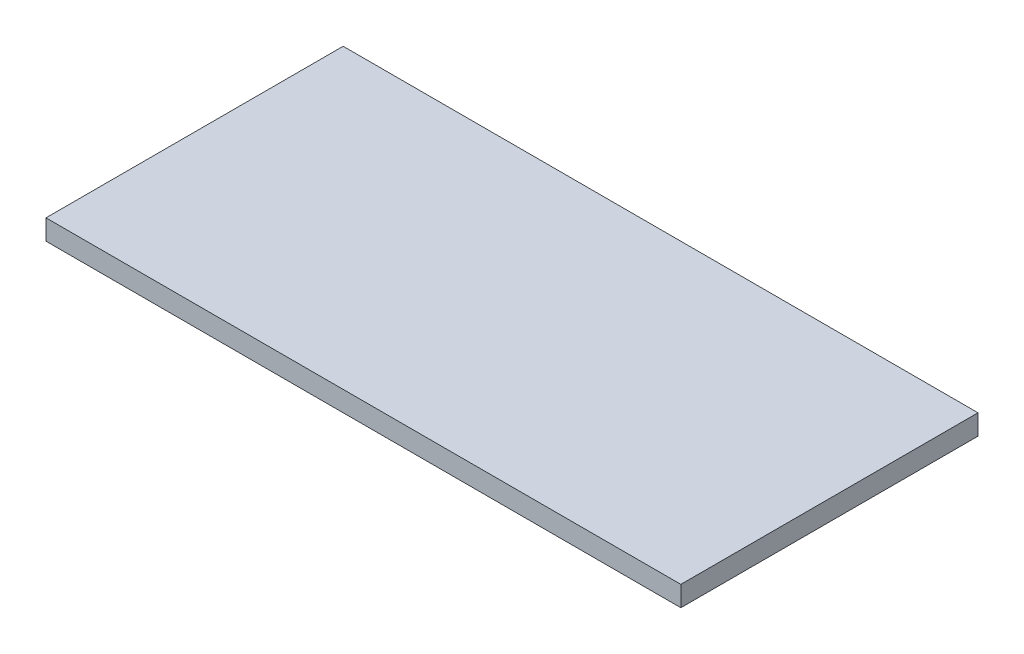
SolidWorks part; units mm, degrees
material "Pine"
ref_plane "Front Plane" through (0, 0, 0) normal (0, 0, 1) x (1, 0, 0)
ref_plane "Top Plane" through (0, 0, 0) normal (0, 1, 0) x (1, 0, 0)
ref_plane "Right Plane" through (0, 0, 0) normal (1, 0, 0) x (0, 0, -1)
sketch "Sketch1" plane through (0, 0, 0) normal (0, 1, 0) x (1, 0, 0)
  line L1 (0, 0) -> (188, 0)
  line L2 (0, 0) -> (0, 88)
  line L3 (0, 88) -> (188, 88)
  line L4 (188, 0) -> (188, 88)
  dimension "D1" = 188
  dimension "D2" = 88
extrude "Boss-Extrude1" add sketch "Sketch1" along normal blind 6
equation "\"BoardThickness\"= 6"
equation "\"D1@Sketch1\"=200-\"BoardThickness\"*2"
equation "\"D2@Sketch1\"=100-\"BoardThickness\"*2"
equation "\"D1@Boss-Extrude1\"=\"BoardThickness\""
